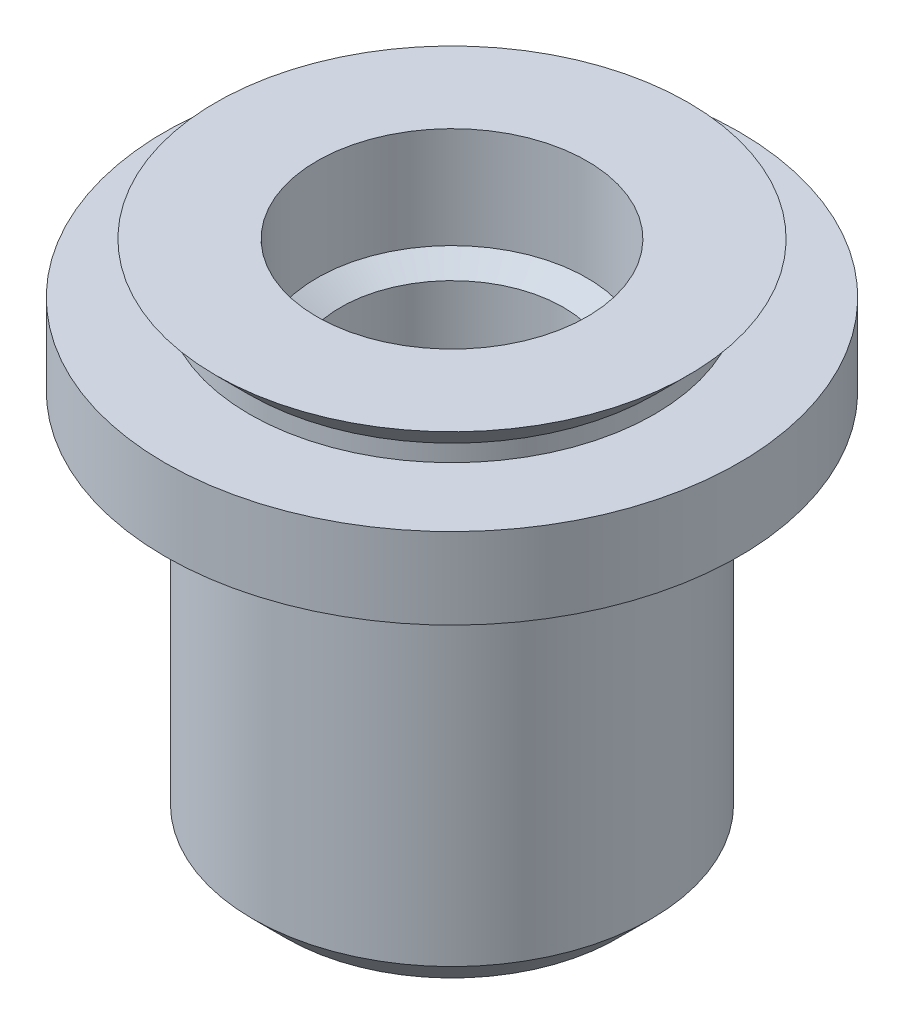
SolidWorks part; units mm, degrees
material "Aço galvanizado"
ref_plane "Plano frontal" through (0, 0, 0) normal (0, 0, 1) x (1, 0, 0)
ref_plane "Plano superior" through (0, 0, 0) normal (0, 1, 0) x (1, 0, 0)
ref_plane "Plano direito" through (0, 0, 0) normal (1, 0, 0) x (0, 0, -1)
sketch "Esboço1" plane through (0, 0, 0) normal (0, 0, 1) x (1, 0, 0)
  line L0 (-2, 0) -> (-3.5, 0)
  line L1 (-3.5, 0) -> (-3, -0.5)
  line L2 (-3, -0.5) -> (-3, -0.75)
  line L3 (-3, -0.75) -> (-4.25, -0.75)
  line L4 (-4.25, -0.75) -> (-4.25, -1.95)
  line L5 (-4.25, -1.95) -> (-2.95, -1.95)
  line L6 (-2.95, -1.95) -> (-2.95, -7.25)
  line L8 (-2.45, -7.75) -> (0, -7.75)
  line L9 (0, -9.8763) -> (0, -2.6019) construction
  line L10 (-2, 0) -> (-2, -1.5)
  line L12 (-1.134, -2) -> (0, -2)
  line L13 (0, -2) -> (0, -7.75)
  line L14 (-2, -2) -> (-2, -7.75) construction
  line L15 (-2.95, -7.25) -> (-2.45, -7.75)
  line L16 (-2, -1.5) -> (-1.134, -2)
  point P4 (-2.95, -7.75)
  point P12 (-2, -2)
  dimension "D3" = 0.5
  dimension "D4" = 45
  dimension "D6" = 2
  dimension "D7" = 0.5
  dimension "D8" = 60
  dimension "D10" = 1
  dimension "D11" = 5.9
  dimension "D5" = 7
  dimension "D2" = 7.75
  dimension "D12" = 0.75
  dimension "D13" = 8.5
  dimension "D14" = 1.2
  dimension "D15" = 2
revolve "Revolução1" add sketch "Esboço1" angle 360 about L13
hole_wizard "Broca de rosquear para tarraxa de M41" positions "Esboço4" profile "Esboço5" hole size "M4" standard "ISO"
sketch "Esboço4" plane through (0, 0, 0) normal (0, 1, 0) x (1, 0, 0)
  point P0 (0, 0)
sketch "Esboço5" plane through (0, 0, 0) normal (1, 0, 0) x (0, 0, 1)
  line L0 (0, 0) -> (0, 7)
  line L1 (0, 7) -> (1.65, 6.0086)
  line L2 (1.65, 6.0086) -> (1.65, 0)
  line L5 (1.65, 0) -> (0, 0)
  line L10 (0, 7) -> (-1.65, 6.0086) construction
  line L11 (0, -6.35) -> (0, 107.95) construction
  dimension "Hole Dia." = 3.3
  dimension "Hole Depth" = 7
  dimension "Drill Angle" = 118
equation "\"D2@Esboço1\"=7+0.75"
equation "\"D12@Esboço1\"=0.75"
